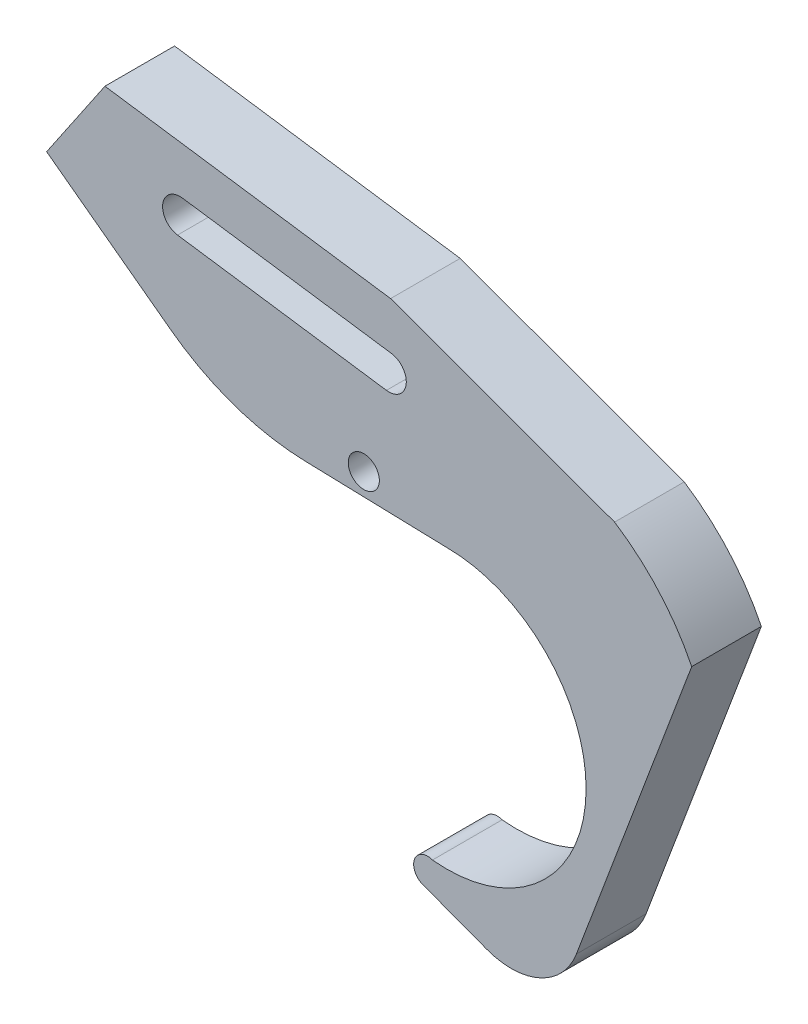
SolidWorks part; units mm, degrees
material "Alloy Steel"
ref_plane "Front Plane" through (0, 0, 0) normal (0, 0, 1) x (1, 0, 0)
ref_plane "Top Plane" through (0, 0, 0) normal (0, 1, 0) x (1, 0, 0)
ref_plane "Right Plane" through (0, 0, 0) normal (1, 0, 0) x (0, 0, -1)
sketch "Sketch1" plane through (0, 0, 0) normal (0, 0, 1) x (1, 0, 0)
  line L0 (-26.8246, 88.7682) -> (25.2746, 81.2743)
  line L10 (-14.8198, 56.3019) -> (-37.4522, 73.1064)
  line L11 (-37.4522, 73.1064) -> (-26.8246, 88.7682)
  line L12 (24.969, 69.541) -> (-13.131, 75.0213) construction
  line L13 (24.517, 66.3984) -> (-13.583, 71.8787)
  line L14 (25.421, 72.6837) -> (-12.679, 78.164)
  line L17 (66.1342, 66.3984) -> (25.2746, 81.2743)
  line L21 (35.5396, 47.0741) -> (9.6961, 47.8078)
  line L25 (35.5396, -3.7259) -> (35.5396, 47.0741) construction
  line L36 (80.2011, 50.5999) -> (59.166, -5.3215)
  line L39 (31.1323, -8.3453) -> (42.8078, -12.7371)
  line L40 (31.1323, -8.3453) -> (32.9208, -3.5906) construction
  circle A0 centre (20.3901, 51.503) radius 2.8384
  arc A1 (24.517, 66.3984) -> (25.421, 72.6837) centre (24.969, 69.541) ccw
  arc A2 (-12.679, 78.164) -> (-13.583, 71.8787) centre (-13.131, 75.0213) ccw
  arc A4 (35.5396, -3.7259) -> (52.6483, 40.4479) centre (35.5396, 21.6741) ccw
  arc A5 (52.6483, 40.4479) -> (35.5396, 47.0741) centre (35.5396, 21.6741) ccw
  circle A6 centre (35.5396, 21.6741) radius 25.4 construction
  arc A7 (35.5396, -3.7259) -> (32.9208, -3.5906) centre (35.5396, 21.6741) cw
  arc A12 (32.9208, -3.5906) -> (31.1323, -8.3453) centre (32.0265, -5.9679) ccw
  arc A13 (59.166, -5.3215) -> (42.8078, -12.7371) centre (47.2791, -0.8502) cw
  arc A14 (80.2011, 50.5999) -> (66.1342, 66.3984) centre (44.5004, 32.9741) ccw
  arc A15 (9.6961, 47.8078) -> (-14.8198, 56.3019) centre (10.9214, 90.9704) cw
  point P4 (28.5202, -10.2501)
  point P5 (30.4886, -16.4162)
  point P16 (5.919, 72.2812)
  point P24 (0, 0)
  point P31 (57.2583, -11.3188)
  point P32 (29.7361, -16.2039)
  point P33 (35.5396, 47.0741)
  point P34 (0, 0)
  point P37 (0, 0)
  point P38 (0, 0)
  dimension "D1" = 19.05
  dimension "D2" = 25.4
  dimension "D5" = 6.35
  dimension "D6" = 43.18
  dimension "D7" = 12.7
  dimension "D8" = 2.54
  dimension "D3" = 168.18
  dimension "D4" = 38.1
extrude "Boss-Extrude2" add sketch "Sketch1" along normal blind 12.7
